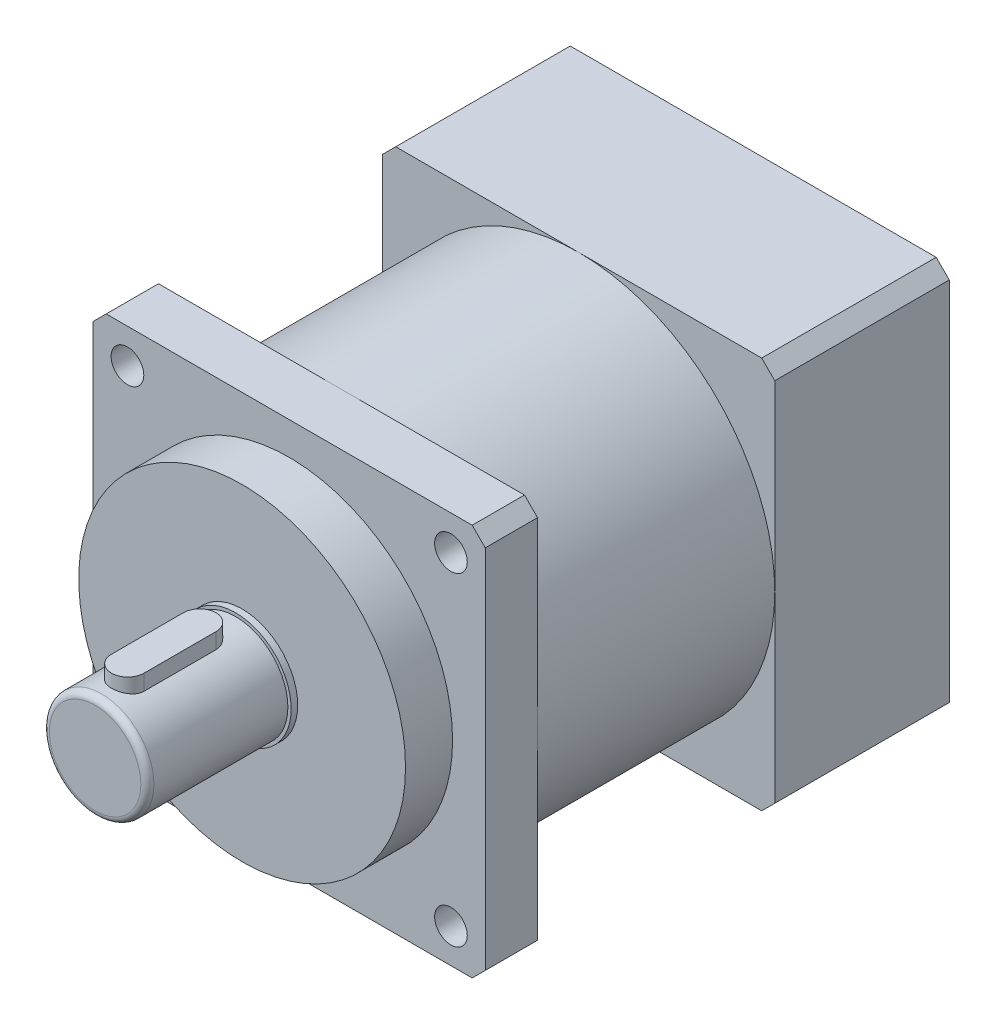
SolidWorks part; units mm, degrees
material "45#"
ref_plane "前视" through (0, 0, 0) normal (0, 0, 1) x (1, 0, 0)
ref_plane "上视" through (0, 0, 0) normal (0, 1, 0) x (1, 0, 0)
ref_plane "右视" through (0, 0, 0) normal (1, 0, 0) x (0, 0, -1)
sketch "草图1" plane through (0, 0, 0) normal (0, 0, 1) x (1, 0, 0)
  line L1 (-30, -30) -> (30, -30)
  line L2 (-30, -30) -> (-30, 30)
  line L3 (-30, 30) -> (30, 30)
  line L4 (30, -30) -> (30, 30)
  line L5 (-30, -30) -> (30, 30) construction
  line L6 (-30, 30) -> (30, -30) construction
  point P0 (0, 0)
  dimension "D1" = 60
  dimension "D2" = 60
extrude "凸台-拉伸1" add sketch "草图1" along normal blind 26.7
sketch "草图2" plane through (0, 0, 0) normal (0, 0, -1) x (-1, 0, 0)
  circle A0 centre (0, 0) radius 25
  dimension "D1" = 50
extrude "切除-拉伸1" cut sketch "草图2" against normal blind 3
sketch "草图3" plane through (0, 0, 3) normal (0, 0, -1) x (-1, 0, 0)
  circle A0 centre (0, 0) radius 7
  dimension "D1" = 14
extrude "切除-拉伸2" cut sketch "草图3" against normal through all
sketch "草图4" plane through (0, 0, 0) normal (0, 0, -1) x (-1, 0, 0)
  line L0 (30, 30) -> (-30, -30) construction
  line L1 (-30, -30) -> (-30, 30) construction
  line L2 (-30, 30) -> (30, -30) construction
  circle A0 centre (0, 0) radius 35 construction
  circle A1 centre (24.7487, 24.7487) radius 1.65
  circle A2 centre (-24.7487, 24.7487) radius 1.65
  circle A3 centre (24.7487, -24.7487) radius 1.65
  circle A4 centre (-24.7487, -24.7487) radius 1.65
  dimension "D1" = 70
  dimension "D2" = 3.3
extrude "切除-拉伸3" cut sketch "草图4" against normal blind 10
sketch "草图5" plane through (0, 0, 26.7) normal (0, 0, 1) x (1, 0, 0)
  circle A0 centre (0, 0) radius 30
  dimension "D1" = 60
extrude "凸台-拉伸2" add sketch "草图5" along normal blind 36.3
sketch "草图6" plane through (0, 0, 63) normal (0, 0, 1) x (1, 0, 0)
  line L1 (-30, 30) -> (30, 30)
  line L2 (-30, 30) -> (-30, -30)
  line L3 (-30, -30) -> (30, -30)
  line L4 (30, 30) -> (30, -30)
extrude "凸台-拉伸3" add sketch "草图6" along normal blind 8
sketch "草图7" plane through (0, 0, 71) normal (0, 0, 1) x (1, 0, 0)
  circle A0 centre (0, 0) radius 25
  dimension "D1" = 50
extrude "凸台-拉伸4" add sketch "草图7" along normal blind 7.2
sketch "草图8" plane through (0, 0, 78.2) normal (0, 0, 1) x (1, 0, 0)
  circle A0 centre (0, 0) radius 8
  dimension "D1" = 16
extrude "凸台-拉伸5" add sketch "草图8" along normal blind 22.5
sketch "草图9" plane through (0, 0, 71) normal (0, 0, 1) x (1, 0, 0)
  circle A0 centre (-24.7487, 24.7487) radius 2.5
  circle A1 centre (24.7487, 24.7487) radius 2.5
  circle A2 centre (24.7487, -24.7487) radius 2.5
  circle A3 centre (-24.7487, -24.7487) radius 2.5
  dimension "D1" = 5
extrude "切除-拉伸4" cut sketch "草图9" against normal blind 8
sketch "草图10" plane through (0, 0, 0) normal (0, 1, 0) x (1, 0, 0)
  line L0 (0, -84.7) -> (0, -95.7) construction
  line L1 (2.5, -84.7) -> (2.5, -95.7)
  line L2 (-2.5, -84.7) -> (-2.5, -95.7)
  line L3 (-8, -100.7) -> (8, -100.7) construction
  arc A0 (2.5, -84.7) -> (-2.5, -84.7) centre (0, -84.7) ccw
  arc A1 (-2.5, -95.7) -> (2.5, -95.7) centre (0, -95.7) ccw
  point P3 (0, -90.2)
  dimension "D3" = 2.5
  dimension "D1" = 11
  dimension "D2" = 5
extrude "凸台-拉伸6" add sketch "草图10" along normal blind 10
chamfer "倒角1" distance 2 angle 45 8 edges at (30, 30, 67) (30, 30, 13.35) (-30, 30, 67) (30, -30, 67) (-30, -30, 67) (30, -30, 13.35) (-30, -30, 13.35) (-30, 30, 13.35)
fillet "圆角1" radius 1 1 edges at (8, 0, 100.7)
sketch "草图11" plane through (0, 0, 78.2) normal (0, 0, 1) x (1, 0, 0)
  circle A0 centre (0, 0) radius 8.5
  dimension "D1" = 17
extrude "凸台-拉伸7" add sketch "草图11" along normal blind 1
